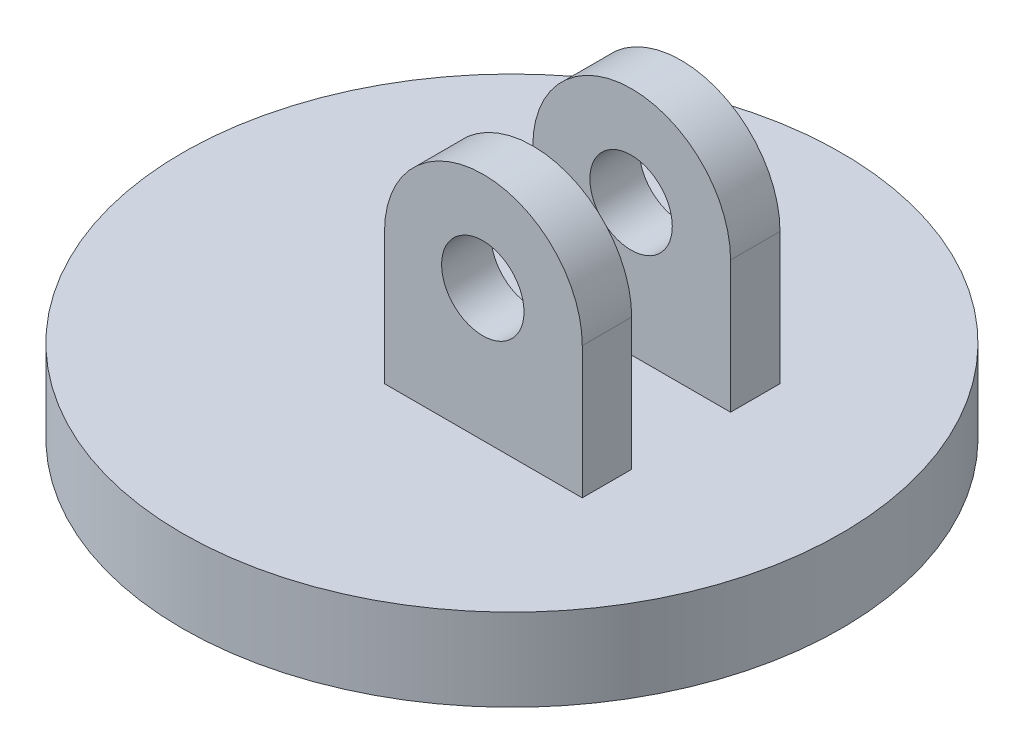
SolidWorks part; units mm, degrees
ref_plane "Front Plane" through (0, 0, 0) normal (0, 0, 1) x (1, 0, 0)
ref_plane "Top Plane" through (0, 0, 0) normal (0, 1, 0) x (1, 0, 0)
ref_plane "Right Plane" through (0, 0, 0) normal (1, 0, 0) x (0, 0, -1)
sketch "Sketch3" plane through (0, 0, 0) normal (0, 1, 0) x (1, 0, 0)
  circle A0 centre (0, 0) radius 2000
  dimension "D1" = 4000
extrude "Boss-Extrude1" add sketch "Sketch3" along normal blind 500
sketch "Sketch4" plane through (0, 500, 0) normal (0, 1, 0) x (1, 0, 0)
  line L0 (0, 0) -> (2000, 0) construction
  line L2 (-173.2051, 600) -> (1026.7949, 600)
  line L3 (-173.2051, 600) -> (-173.2051, 300)
  line L4 (-173.2051, 300) -> (1026.7949, 300)
  line L5 (1026.7949, 600) -> (1026.7949, 300)
  circle A0 centre (0, 0) radius 2000 construction
  dimension "D1" = 300
  dimension "D2" = 1200
  dimension "D3" = 300
extrude "Boss-Extrude2" add sketch "Sketch4" along normal blind 800
sketch "Sketch6" plane through (0, 0, -300) normal (0, 0, 1) x (1, 0, 0)
  line L4 (-173.2051, 500) -> (1026.7949, 500)
  line L5 (1026.7949, 500) -> (1026.7949, 1300)
  line L6 (1026.7949, 1300) -> (-173.2051, 1300)
  line L7 (-173.2051, 1300) -> (-173.2051, 500)
  line L8 (-173.2051, 500) -> (1026.7949, 500)
  line L9 (1026.7949, 500) -> (1026.7949, 1300)
  line L11 (-173.2051, 1300) -> (-173.2051, 500)
  arc A0 (-173.2051, 1300) -> (1026.7949, 1300) centre (426.7949, 1300) cw
  dimension "D1" = 0
extrude "Boss-Extrude3" add sketch "Sketch6" against normal blind 300
sketch "Sketch8" plane through (0, 500, 0) normal (0, 1, 0) x (1, 0, 0)
  line L0 (0, 0) -> (2000, 0) construction
  circle A1 centre (0, 0) radius 2000 construction
sketch "Sketch11" plane through (0, 500, 0) normal (0, 1, 0) x (1, 0, 0)
  line L0 (0, 0) -> (2000, 0) construction
  line L1 (-173.2051, -300) -> (1026.7949, -300)
  line L2 (-173.2051, -300) -> (-173.2051, -600)
  line L3 (-173.2051, -600) -> (1026.7949, -600)
  line L4 (1026.7949, -300) -> (1026.7949, -600)
  dimension "D1" = 300
  dimension "D2" = 1200
  dimension "D3" = 300
extrude "Boss-Extrude4" add sketch "Sketch11" along normal blind 800
sketch "Sketch12" plane through (0, 0, 600) normal (0, 0, 1) x (1, 0, 0)
  line L0 (-173.2051, 1300) -> (1026.7949, 1300)
  arc A0 (-173.2051, 1300) -> (1026.7949, 1300) centre (426.7949, 1300) cw
extrude "Boss-Extrude5" add sketch "Sketch12" against normal blind 300
sketch "Sketch13" plane through (0, 0, 600) normal (0, 0, 1) x (1, 0, 0)
  circle A0 centre (423.1635, 1300.011) radius 250
  arc A1 (1026.7949, 1300) -> (-173.2051, 1300) centre (426.7949, 1300) ccw construction
  point P5 (426.7949, 1900)
  dimension "D1" = 500
  dimension "D2" = 600
extrude "Cut-Extrude1" cut sketch "Sketch13" along direction (0, 0, 1) on the side against the normal through all both and the other way through all
